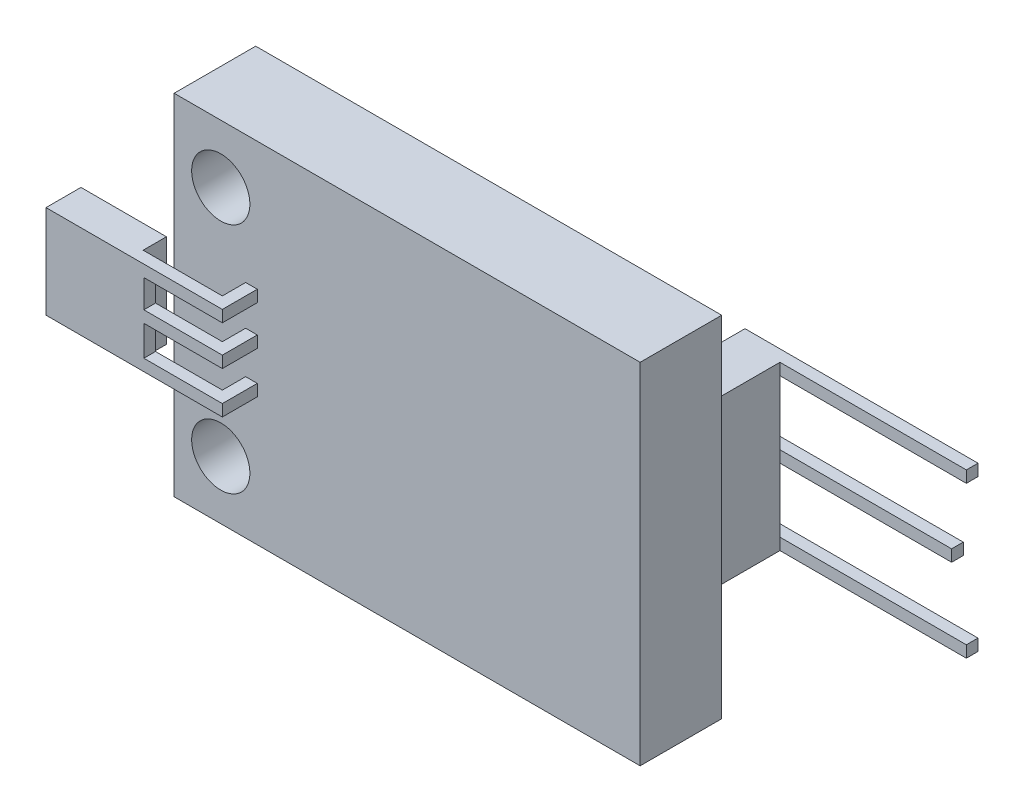
SolidWorks part; units mm, degrees
material "pcb"
ref_plane "Front Plane" through (0, 0, 0) normal (0, 0, 1) x (1, 0, 0)
ref_plane "Top Plane" through (0, 0, 0) normal (0, 1, 0) x (1, 0, 0)
ref_plane "Right Plane" through (0, 0, 0) normal (1, 0, 0) x (0, 0, -1)
sketch "Sketch1" plane through (0, 0, 0) normal (0, 0, 1) x (1, 0, 0)
  line L1 (-10, -7.5) -> (10, -7.5)
  line L2 (-10, -7.5) -> (-10, 7.5)
  line L3 (-10, 7.5) -> (10, 7.5)
  line L4 (10, -7.5) -> (10, 7.5)
  line L5 (-10, -7.5) -> (10, 7.5) construction
  line L6 (-10, 7.5) -> (10, -7.5) construction
  point P0 (0, 0)
  dimension "D1" = 20
  dimension "D2" = 15
extrude "Boss-Extrude1" add sketch "Sketch1" along normal blind 3.5
sketch "Sketch2" plane through (0, 0, 3.5) normal (0, 0, 1) x (1, 0, 0)
  line L0 (-10, 0) -> (-14, 0) construction
  line L1 (-10, 7.5) -> (-10, -7.5) construction
  line L2 (-10, 2) -> (-6.4316, 2)
  line L3 (-14, -2) -> (-10, -2)
  line L4 (-14, -2) -> (-14, 2)
  line L5 (-14, 2) -> (-10, 2)
  line L6 (-10, -2) -> (-10, 2) construction
  line L7 (-14, -2) -> (-10, 2) construction
  line L8 (-14, 2) -> (-10, -2) construction
  line L9 (-6.4316, 2) -> (-6.4316, 1.5)
  line L10 (-6.4316, 1.5) -> (-9.8, 1.5)
  line L12 (-9.8, 0.3) -> (-6.4316, 0.3)
  line L13 (-6.4316, 0.3) -> (-6.4316, -0.2)
  line L14 (-6.4316, -0.2) -> (-9.8, -0.2)
  line L16 (-9.8, -1.5) -> (-6.4316, -1.5)
  line L17 (-6.4316, -1.5) -> (-6.4316, -2)
  line L18 (-6.4316, -2) -> (-10, -2)
  line L19 (-10, 1.5) -> (-10, 0.3)
  line L20 (-9.8, 1.5) -> (-9.8, 0.3)
  line L21 (-9.8, -0.2) -> (-9.8, -1.5)
  point P5 (-12, 0)
  line M19 (-10, 7.5) -> (-10, -7.5)
  dimension "D1" = 4
  dimension "D2" = 4
  dimension "D3" = 0.5
  dimension "D4" = 0.5
  dimension "D5" = 0.2
  dimension "D6" = 0.5
  dimension "D7" = 0.2
extrude "Boss-Extrude8" add sketch "Sketch2" along normal blind 1.5 contours L21 L14 L13 L12 L20 L10 L9 L2 L18 L17 L16 M19 | L5 L4 L3 M19
sketch "Sketch3" plane through (0, -2, 0) normal (0, -1, 0) x (1, 0, 0)
  line L0 (-10.3316, 3.5) -> (-10.3316, 4.5)
  line L1 (-10, 3.5) -> (-14, 3.5) construction
  line L2 (-10.3316, 4.5) -> (-6.9316, 4.5)
  line L3 (-6.9316, 4.5) -> (-6.9316, 3.5)
  line L4 (-10, 3.5) -> (10, 3.5) construction
  line L5 (-6.9316, 3.5) -> (-10.3316, 3.5)
  line L6 (-6.4316, 5) -> (-14, 5) construction
  line L7 (-6.4316, 5) -> (-6.4316, 3.5) construction
  dimension "D1" = 3.4
  dimension "D2" = 0.5
  dimension "D3" = 0.5
extrude "Cut-Extrude1" cut sketch "Sketch3" against normal through all
sketch "Sketch7" plane through (0, 0, 0) normal (0, 0, -1) x (-1, 0, 0)
  line L0 (10, 0) -> (-10, 0) construction
  line L1 (10, 7.5) -> (10, -7.5) construction
  line L2 (-10, -7.5) -> (-10, 7.5) construction
  line L3 (8, 0) -> (8, -5) construction
  circle A0 centre (8, -5) radius 1.25
  circle A1 centre (8, 5) radius 1.25
  dimension "D1" = 2.5
  dimension "D2" = 2
  dimension "D3" = 5
extrude "Cut-Extrude4" cut sketch "Sketch7" against normal through all
sketch "Sketch8" plane through (0, 0, 0) normal (0, 0, -1) x (-1, 0, 0)
  line L0 (-8.5578, 0) -> (-15.9496, 0) construction
  line L1 (-10, -7.5) -> (-10, 7.5) construction
  line L2 (-7, 3.5) -> (-17, 3.5)
  line L3 (-7, 3.5) -> (-7, -3.5)
  line L4 (-7, -3.5) -> (-17, -3.5)
  line L5 (-17, 3.5) -> (-17, -3.5)
  dimension "D1" = 7
  dimension "D2" = 3
  dimension "D3" = 3.5
  dimension "D4" = 7
extrude "Boss-Extrude9" add sketch "Sketch8" along normal blind 4
sketch "Sketch9" plane through (0, 0, -4) normal (0, 0, -1) x (-1, 0, 0)
  line L13 (-17, -3.5) -> (-7, -3.5) construction
  line L14 (-6, -3) -> (-18, -3)
  line L15 (-18, -3) -> (-18, 3)
  line L16 (-18, 3) -> (-6, 3)
  line L17 (-6, 3) -> (-6, 0.25)
  line L18 (-6, 0.25) -> (-16.368, 0.25)
  line L19 (-16.368, 0.25) -> (-16.368, -0.25)
  line L20 (-16.368, -0.25) -> (-6, -0.25)
  line L21 (-6, -0.25) -> (-6, -3)
  line L22 (-7, -3.5) -> (-7, 3.5) construction
  line L23 (-17, 3.5) -> (-17, -3.5) construction
  line L24 (-7, 3.5) -> (-17, 3.5) construction
  line L25 (-16.368, 0) -> (-5.8182, 0) construction
  point P18 (-18, 0)
  dimension "D1" = 1
  dimension "D2" = 1
  dimension "D3" = 0.5
  dimension "D4" = 0.5
  dimension "D5" = 0.5
extrude "Cut-Extrude5" cut sketch "Sketch9" against normal blind 0.5
sketch "Sketch10" plane through (0, 3.5, 0) normal (0, 1, 0) x (1, 0, 0)
  line L0 (7, 4) -> (17, 4) construction
  line L1 (17, 0) -> (9, 0)
  line L2 (17, 0) -> (17, 3.5)
  line L3 (17, 3.5) -> (9, 3.5)
  line L4 (9, 0) -> (9, 3.5)
  line L5 (7, 4) -> (7, 0) construction
  dimension "D1" = 0.5
  dimension "D2" = 2
extrude "Cut-Extrude6" cut sketch "Sketch10" against normal through all
